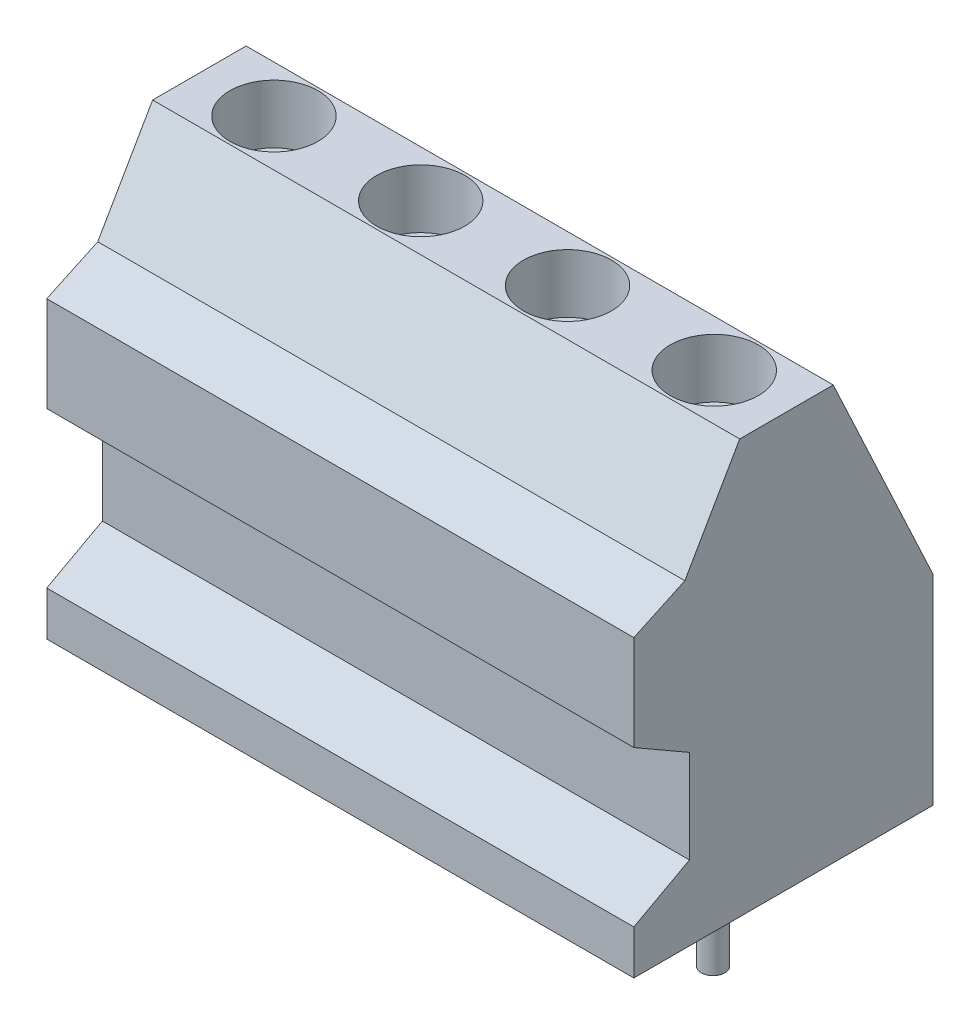
SolidWorks part; units mm, degrees
ref_plane "前视基准面" through (0, 0, 0) normal (0, 0, 1) x (1, 0, 0)
ref_plane "上视基准面" through (0, 0, 0) normal (0, 1, 0) x (1, 0, 0)
ref_plane "右视基准面" through (0, 0, 0) normal (1, 0, 0) x (0, 0, -1)
sketch "草图1" plane through (0, 0, 0) normal (1, 0, 0) x (0, 0, -1)
  line L0 (0, 30.1837) -> (0, -33.3778) construction
  line L1 (0, 0) -> (5, 0)
  line L2 (5, 0) -> (5, 6.7989)
  line L3 (5, 6.7989) -> (1.5929, 14.1)
  line L4 (1.5929, 14.1) -> (-1.5929, 14.1)
  line L5 (-1.5929, 14.1) -> (-3.4622, 10.8528)
  line L6 (-3.4622, 10.8528) -> (-5.2, 10.0418)
  line L7 (-5.2, 10.0418) -> (-5.2, 6.7989)
  line L8 (-5.2, 6.7989) -> (-3.3058, 5.7085)
  line L9 (-3.3058, 5.7085) -> (-3.3058, 2.5346)
  line L10 (-3.3058, 2.5346) -> (-5.2, 1.5061)
  line L11 (-5.2, 1.5061) -> (-5.2, 0)
  line L12 (-5.2, 0) -> (0, 0)
  point P7 (0, 0)
  dimension "D1" = 5
  dimension "D2" = 14.1
  dimension "D3" = 10.2
extrude "凸台-拉伸1" add sketch "草图1" along normal blind 20
sketch "草图2" plane through (0, 14.1, 0) normal (0, 1, 0) x (1, 0, 0)
  line L0 (-3.4571, 0) -> (11.4473, 0) construction
  line L1 (0, 1.5929) -> (0, -1.5929) construction
  circle A0 centre (2.54, 0) radius 1.5
  circle A1 centre (7.54, 0) radius 1.5
  circle A2 centre (12.54, 0) radius 1.5
  circle A3 centre (17.54, 0) radius 1.5
  dimension "D3" = 3
  dimension "D1" = 2.54
  dimension "D2" = 4
extrude "切除-拉伸1" cut sketch "草图2" against normal blind 2
sketch "草图3" plane through (0, 0, 0) normal (0, -1, 0) x (1, 0, 0)
  line L0 (-3.0899, 0) -> (13.0228, 0) construction
  line L1 (0, 5.2) -> (0, -5) construction
  circle A0 centre (2.5, 0) radius 0.4
  circle A1 centre (7.5, 0) radius 0.4
  circle A2 centre (12.5, 0) radius 0.4
  circle A3 centre (17.5, 0) radius 0.4
  dimension "D1" = 0.8
  dimension "D2" = 2.5
  dimension "D3" = 4
extrude "凸台-拉伸2" add sketch "草图3" along normal blind 3.5
